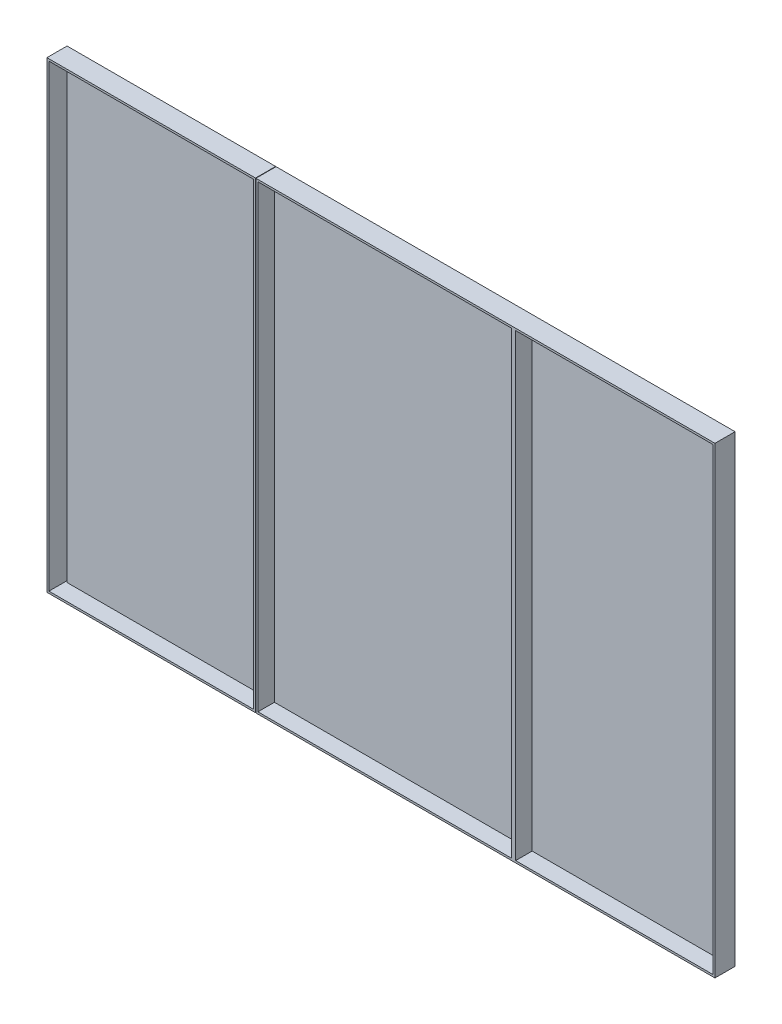
SolidWorks part; units mm, degrees
ref_plane "Plan de face" through (0, 0, 0) normal (0, 0, 1) x (1, 0, 0)
ref_plane "Plan de dessus" through (0, 0, 0) normal (0, 1, 0) x (1, 0, 0)
ref_plane "Plan de droite" through (0, 0, 0) normal (1, 0, 0) x (0, 0, -1)
sketch "Esquisse1" plane through (0, 0, 0) normal (0, 0, 1) x (1, 0, 0)
  line L0 (0, 0) -> (0, 570)
  line L5 (0, 570) -> (250, 570)
  line L6 (250, 570) -> (250, 0)
  line L7 (250, 0) -> (0, 0)
  dimension "D1" = 250
  dimension "D2" = 570
extrude "Boss.-Extru.2" add sketch "Esquisse1" along normal blind 2
sketch "Esquisse11" plane through (0, 0, 0) normal (0, 0, -1) x (-1, 0, 0)
  line L0 (-254.5, 572.5) -> (-254.5, -2.5)
  line L1 (-252, 570) -> (2, 570)
  line L2 (-252, 570) -> (-252, 0)
  line L3 (-252, 0) -> (2, 0)
  line L4 (2, 570) -> (2, 0)
  line L5 (-254.5, -2.5) -> (4.5, -2.5)
  line L6 (4.5, 572.5) -> (4.5, -2.5)
  line L7 (-254.5, 572.5) -> (4.5, 572.5)
  line L8 (-250, 0) -> (-250, 570) construction
  line L9 (0, 570) -> (0, 0) construction
  dimension "D2" = 254
  dimension "D3" = 259
  dimension "D4" = 2
  dimension "D5" = 2
  dimension "D1" = 2.5
extrude "Boss.-Extru.12" add sketch "Esquisse11" against normal blind 22.5 separate body
sketch "Esquisse12" plane through (0, 0, 0) normal (0, 0, -1) x (-1, 0, 0)
  line L0 (-229.5, 547.5) -> (-229.5, 22.5)
  line L1 (-254.5, 572.5) -> (4.5, 572.5)
  line L2 (-254.5, 572.5) -> (-254.5, -2.5)
  line L3 (-254.5, -2.5) -> (4.5, -2.5)
  line L4 (4.5, 572.5) -> (4.5, -2.5)
  line L5 (-229.5, 22.5) -> (-20.5, 22.5)
  line L6 (-20.5, 547.5) -> (-20.5, 22.5)
  line L7 (-229.5, 547.5) -> (-20.5, 547.5)
  dimension "D1" = 25
extrude "Boss.-Extru.13" add sketch "Esquisse12" along normal blind 2.5
sketch "Esquisse13" plane through (0, 0, 0) normal (0, 0, -1) x (-1, 0, 0)
  line L1 (-255.0093, 572.5) -> (-575.0093, 572.5)
  line L2 (-255.0093, 572.5) -> (-255.0093, -2.5)
  line L3 (-255.0093, -2.5) -> (-575.0093, -2.5)
  line L4 (-575.0093, 572.5) -> (-575.0093, -2.5)
  line L6 (-257.5093, 570) -> (-572.5093, 570)
  line L7 (-572.5093, 570) -> (-572.5093, 0)
  line L8 (-257.5093, 0) -> (-572.5093, 0)
  line L9 (-257.5093, 570) -> (-257.5093, 0)
  line L10 (4.5, 572.5) -> (-254.5, 572.5) construction
  dimension "D1" = 320
  dimension "D2" = 575
  dimension "D3" = 0
  dimension "D5" = 2.5
extrude "Boss.-Extru.14" add sketch "Esquisse13" against normal blind 22.5 separate body
sketch "Esquisse14" plane through (0, 0, 0) normal (0, 0, -1) x (-1, 0, 0)
  line L0 (-550.0093, 547.5) -> (-550.0093, 22.5)
  line L1 (-575.0093, 572.5) -> (-255.0093, 572.5)
  line L2 (-575.0093, 572.5) -> (-575.0093, -2.5)
  line L3 (-575.0093, -2.5) -> (-255.0093, -2.5)
  line L4 (-255.0093, 572.5) -> (-255.0093, -2.5)
  line L5 (-550.0093, 22.5) -> (-280.0093, 22.5)
  line L6 (-280.0093, 547.5) -> (-280.0093, 22.5)
  line L7 (-550.0093, 547.5) -> (-280.0093, 547.5)
  dimension "D1" = 25
extrude "Boss.-Extru.15" add sketch "Esquisse14" along normal blind 2.5
sketch "Esquisse15" plane through (0, 0, 0) normal (0, 0, 1) x (1, 0, 0)
  line L1 (257.5093, 570) -> (572.5093, 570)
  line L2 (257.5093, 570) -> (257.5093, 0)
  line L3 (257.5093, 0) -> (572.5093, 0)
  line L4 (572.5093, 570) -> (572.5093, 0)
extrude "Boss.-Extru.16" add sketch "Esquisse15" along normal blind 2 separate body
sketch "Esquisse18" plane through (0, 0, 0) normal (0, 0, -1) x (-1, 0, 0)
  line L0 (-575.0093, 572.5) -> (-575.0093, -2.5) construction
  line L1 (-575.0093, 572.5) -> (-825.0093, 572.5)
  line L2 (-575.0093, 572.5) -> (-575.0093, -2.5)
  line L3 (-575.0093, -2.5) -> (-825.0093, -2.5)
  line L4 (-825.0093, 572.5) -> (-825.0093, -2.5)
  line L5 (-825.0093, 285) -> (-644.7983, 285) construction
  line L6 (-575.0093, 285) -> (-644.7983, 285) construction
  line L7 (-577.5093, 570) -> (-822.5093, 570)
  line L8 (-822.5093, 570) -> (-822.5093, 0)
  line L9 (-577.5093, 0) -> (-822.5093, 0)
  line L10 (-577.5093, 570) -> (-577.5093, 0)
  dimension "D1" = 575
  dimension "D2" = 250
  dimension "D3" = 2.5
extrude "Boss.-Extru.19" add sketch "Esquisse18" against normal blind 22.5
sketch "Esquisse19" plane through (0, 0, 0) normal (0, 0, -1) x (-1, 0, 0)
  line L0 (-800.0093, 547.5) -> (-800.0093, 22.5)
  line L1 (-825.0093, 572.5) -> (-575.0093, 572.5)
  line L2 (-825.0093, 572.5) -> (-825.0093, -2.5)
  line L3 (-825.0093, -2.5) -> (-575.0093, -2.5)
  line L4 (-575.0093, 572.5) -> (-575.0093, -2.5)
  line L5 (-800.0093, 22.5) -> (-600.0093, 22.5)
  line L6 (-600.0093, 547.5) -> (-600.0093, 22.5)
  line L7 (-800.0093, 547.5) -> (-600.0093, 547.5)
  dimension "D1" = 25
extrude "Boss.-Extru.20" add sketch "Esquisse19" along normal blind 2.5
sketch "Esquisse20" plane through (0, 0, 0) normal (0, 0, 1) x (1, 0, 0)
  line L1 (577.5093, 570) -> (822.5093, 570)
  line L2 (577.5093, 570) -> (577.5093, 0)
  line L3 (577.5093, 0) -> (822.5093, 0)
  line L4 (822.5093, 570) -> (822.5093, 0)
extrude "Boss.-Extru.21" add sketch "Esquisse20" along normal blind 2 separate body
